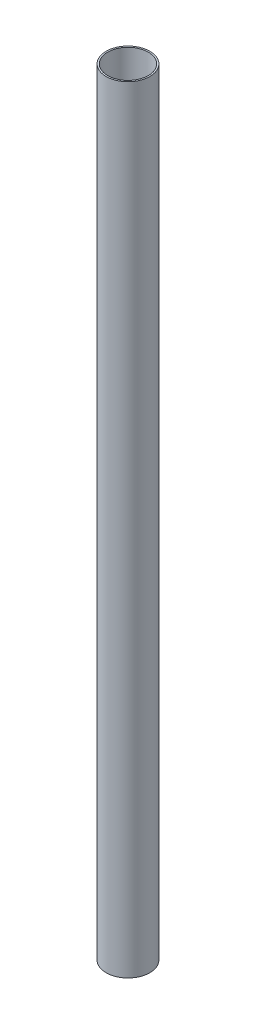
SolidWorks part; units mm, degrees
ref_plane "Front Plane" through (0, 0, 0) normal (0, 0, 1) x (1, 0, 0)
ref_plane "Top Plane" through (0, 0, 0) normal (0, 1, 0) x (1, 0, 0)
ref_plane "Right Plane" through (0, 0, 0) normal (1, 0, 0) x (0, 0, -1)
sketch "Sketch1" plane through (0, 0, 0) normal (0, 1, 0) x (1, 0, 0)
  circle A0 centre (0, 0) radius 13.9827
  circle A1 centre (0, 0) radius 15.0495
  dimension "D1" = 27.9654
  dimension "D2" = 30.099
extrude "Boss-Extrude1" add sketch "Sketch1" along normal blind 534
